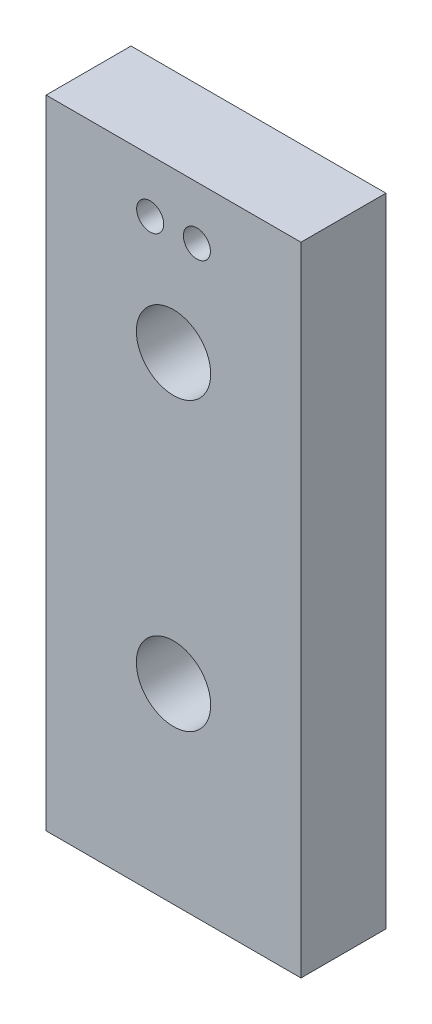
SolidWorks part; units mm, degrees
ref_plane "Front Plane" through (0, 0, 0) normal (0, 0, 1) x (1, 0, 0)
ref_plane "Top Plane" through (0, 0, 0) normal (0, 1, 0) x (1, 0, 0)
ref_plane "Right Plane" through (0, 0, 0) normal (1, 0, 0) x (0, 0, -1)
sketch "Sketch1" plane through (0, 0, 0) normal (0, 0, 1) x (1, 0, 0)
  line L0 (0, 0) -> (0, 95.25) construction
  line L1 (-19.05, 0) -> (19.05, 0)
  line L2 (-19.05, 0) -> (-19.05, 95.25)
  line L3 (-19.05, 95.25) -> (19.05, 95.25)
  line L4 (19.05, 0) -> (19.05, 95.25)
  circle A0 centre (0, 28.575) radius 5.5563
  circle A1 centre (0, 71.4375) radius 5.5562
  dimension "D3" = 11.1125
  dimension "D4" = 11.1125
  dimension "D1" = 95.25
  dimension "D2" = 38.1
  dimension "D5" = 28.575
  dimension "D6" = 71.4375
extrude "Boss-Extrude1" add sketch "Sketch1" along normal blind 12.7
hole_wizard "#10-32 Tapped Hole1" positions "Sketch3" profile "Sketch2" tap size "#10-32" standard "ANSI Inch"
sketch "Sketch3" plane through (0, 0, 0) normal (0, -1, 0) x (-1, 0, 0)
  line L0 (19.05, -12.7) -> (19.05, 0) construction
  line L1 (-19.05, -12.7) -> (-19.05, 0) construction
  line L2 (19.05, 0) -> (-19.05, 0) construction
  point P0 (13.97, -6.35)
  point P2 (-13.97, -6.35)
  dimension "D1" = 5.08
  dimension "D2" = 5.08
  dimension "D3" = 6.35
sketch "Sketch2" plane through (-13.97, 0, 6.35) normal (1, 0, 0) x (0, 0, -1)
  line L0 (0, 0) -> (0, 17.0883)
  line L1 (0, 17.0883) -> (2.0193, 15.875)
  line L2 (2.0193, 15.875) -> (2.0193, 0)
  line L5 (2.0193, 0) -> (0, 0)
  line L10 (0, 17.0883) -> (-2.0193, 15.875) construction
  line L11 (0, -6.35) -> (0, 107.95) construction
  dimension "Tap Drill Dia." = 4.0386
  dimension "Tap Drill Depth" = 15.875
  dimension "Drill Angle" = 118
cosmetic thread "Hole Thread1" parameters "D1"=9.525, "D2"=4.826
cosmetic thread "Hole Thread2" parameters "D1"=9.525, "D2"=4.826
hole_wizard "#10-32 Tapped Hole2" positions "Sketch5" profile "Sketch6" tap size "#10-32" standard "ANSI Inch" end condition through all
sketch "Sketch5" plane through (0, 0, 12.7) normal (0, 0, 1) x (1, 0, 0)
  line L0 (-19.05, 0) -> (19.05, 0) construction
  line L2 (-3.4925, 87.3125) -> (3.4925, 87.3125) construction
  point P0 (-3.4925, 87.3125)
  point P2 (3.4925, 87.3125)
  dimension "D1" = 87.3125
  dimension "D2" = 6.985
  dimension "D3" = 3.4925
sketch "Sketch6" plane through (-3.4925, 87.3125, 12.7) normal (1, 0, 0) x (0, -1, 0)
  line L0 (0, 0) -> (0, 12.7)
  line L1 (0, 12.7) -> (2.0193, 12.7)
  line L2 (2.0193, 12.7) -> (2.0193, 0)
  line L5 (2.0193, 0) -> (0, 0)
  line L11 (0, -6.35) -> (0, 107.95) construction
  dimension "Thru Tap Drill Dia." = 4.0386
  dimension "Thru Tap Drill Depth" = 12.7
cosmetic thread "Hole Thread3" parameters "D2"=4.826
cosmetic thread "Hole Thread4" parameters "D2"=4.826
equation "\"D3@Sketch5\"=\"D2@Sketch5\"/2"
